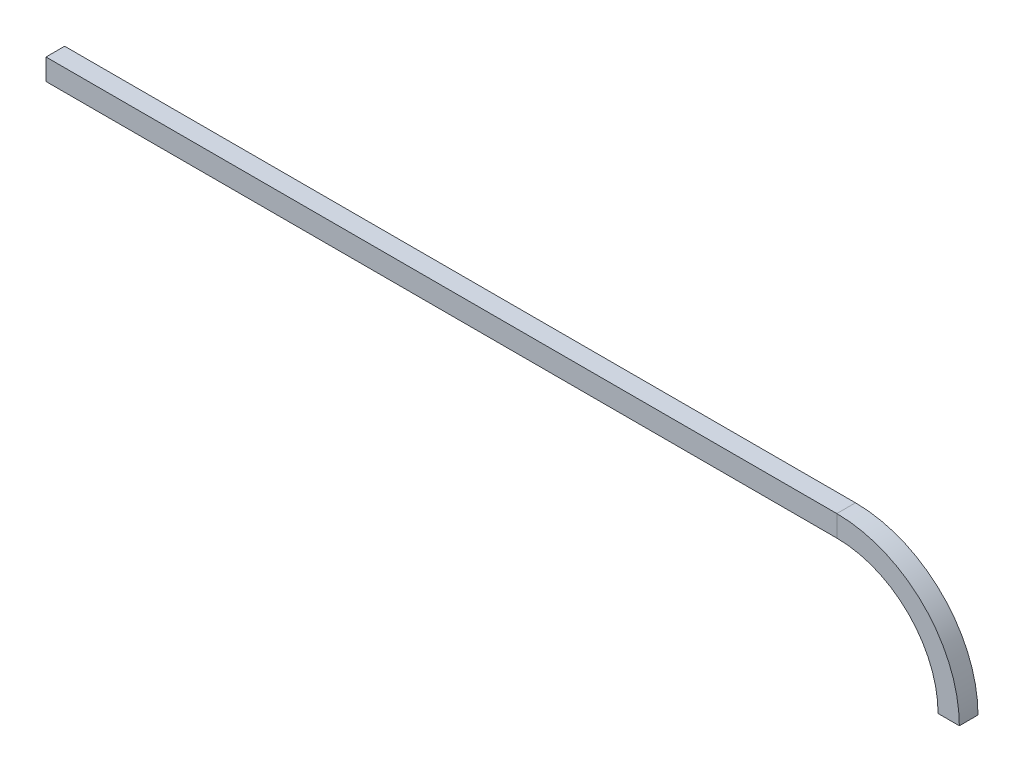
SolidWorks part; units mm, degrees
material "Rubber"
ref_plane "Front" through (0, 0, 0) normal (0, 0, 1) x (1, 0, 0)
ref_plane "Top" through (0, 0, 0) normal (0, 1, 0) x (1, 0, 0)
ref_plane "Right" through (0, 0, 0) normal (1, 0, 0) x (0, 0, -1)
sketch "Sketch2" plane through (0, 0, 0) normal (0, 0, 1) x (1, 0, 0)
  line L0 (0, 0) -> (53.848, 0)
  line L1 (0, 0) -> (0, -7.62) construction
  line L2 (0, -7.62) -> (61.468, -7.62) construction
  arc A0 (53.848, 0) -> (61.468, -7.62) centre (53.848, -7.62) cw
  dimension "D3" = 7.62
  dimension "D1" = 7.62
  dimension "D2" = 53.848
sketch "Sketch3" plane through (0, 0, 0) normal (1, 0, 0) x (0, 0, -1)
  line L0 (-0.635, 0.7239) -> (0.635, -0.7239) construction
  line L3 (-0.635, 0.7239) -> (0.635, 0.7239)
  line L4 (-0.635, 0.7239) -> (-0.635, -0.7239)
  line L5 (-0.635, -0.7239) -> (0.635, -0.7239)
  line L6 (0.635, 0.7239) -> (0.635, -0.7239)
  point P4 (0, 0)
  dimension "D2" = 1.27
  dimension "D1" = 1.4478
sweep "Sweep2" add profiles "Sketch3" path "Sketch2"
sketch "Sketch9" plane through (0, 0, 0) normal (-1, 0, 0) x (0, 0, 1)
  line L1 (-0.3175, -0.3175) -> (0.3175, -0.3175)
  line L2 (-0.3175, -0.3175) -> (-0.3175, 0.3175)
  line L3 (-0.3175, 0.3175) -> (0.3175, 0.3175)
  line L4 (0.3175, -0.3175) -> (0.3175, 0.3175)
  line L5 (-0.3175, -0.3175) -> (0.3175, 0.3175) construction
  line L6 (-0.3175, 0.3175) -> (0.3175, -0.3175) construction
  point P0 (0, 0)
  dimension "D1" = 0.635
  dimension "D2" = 0.635
extrude "Cut-Extrude1" cut sketch "Sketch9" against normal blind 50.8
